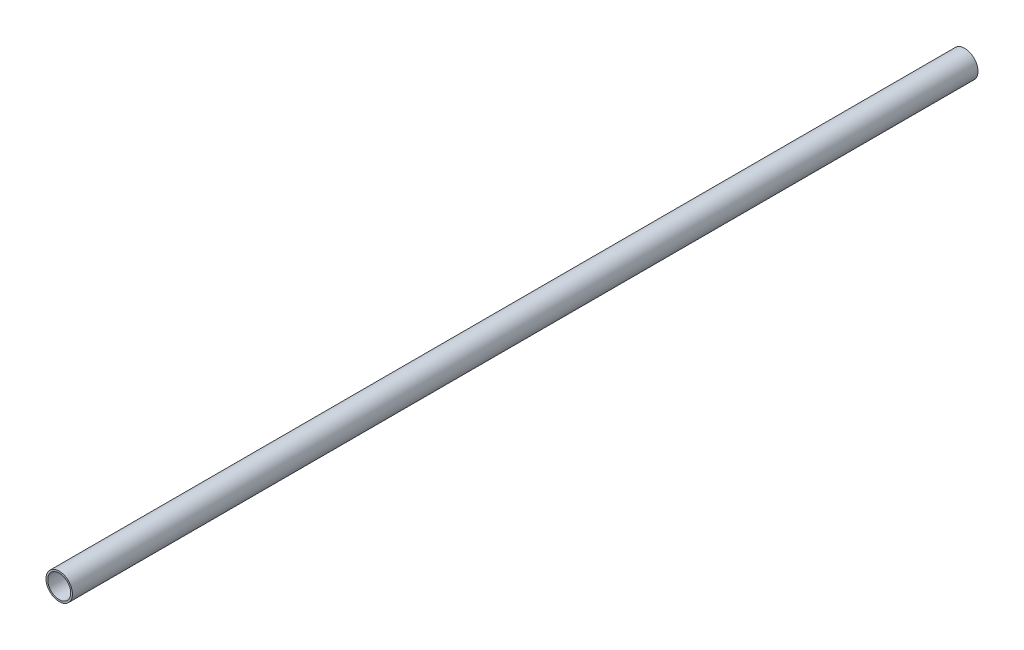
SolidWorks part; units mm, degrees
ref_plane "Front Plane" through (0, 0, 0) normal (0, 0, 1) x (1, 0, 0)
ref_plane "Top Plane" through (0, 0, 0) normal (0, 1, 0) x (1, 0, 0)
ref_plane "Right Plane" through (0, 0, 0) normal (1, 0, 0) x (0, 0, -1)
sketch "Sketch1" plane through (0, 0, 0) normal (0, 0, 1) x (1, 0, 0)
  circle A0 centre (0, 0) radius 11.1125
  circle A1 centre (0, 0) radius 9.6395
extrude "Boss-Extrude1" add sketch "Sketch1" along normal blind 760
